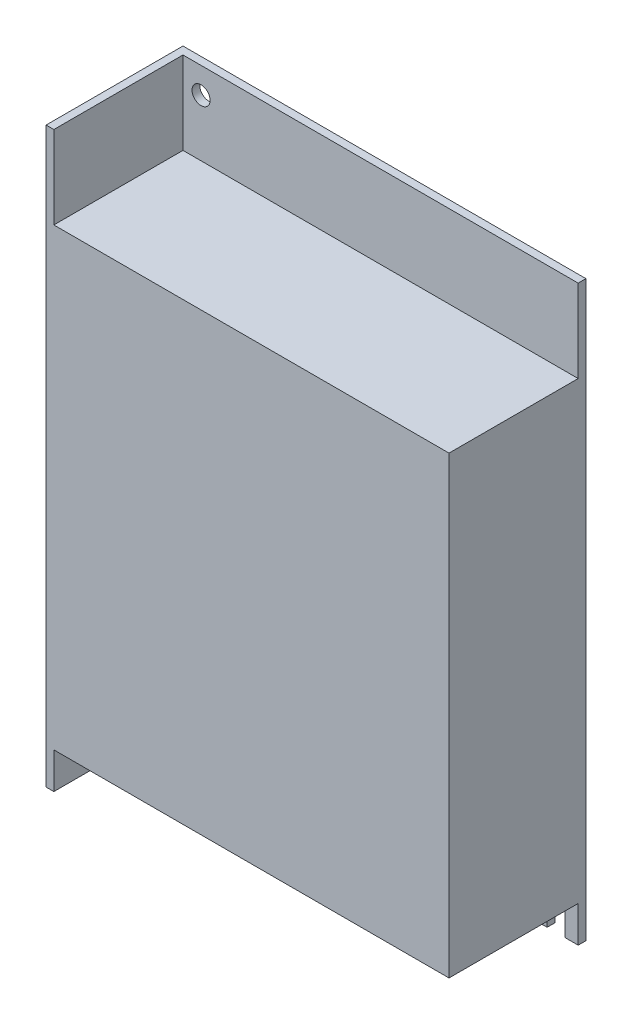
SolidWorks part; units mm, degrees
ref_plane "Plan de face" through (0, 0, 0) normal (0, 0, 1) x (1, 0, 0)
ref_plane "Plan de dessus" through (0, 0, 0) normal (0, 1, 0) x (1, 0, 0)
ref_plane "Plan de droite" through (0, 0, 0) normal (1, 0, 0) x (0, 0, -1)
sketch "Esquisse1" plane through (0, 0, 0) normal (0, 0, 1) x (1, 0, 0)
  line L0 (72, 4.25) -> (72, 0)
  line L1 (0, 0) -> (78, 0)
  line L2 (0, 0) -> (0, 111)
  line L3 (0, 111) -> (78, 111)
  line L4 (78, 0) -> (78, 111)
  line L5 (75.5, 4.25) -> (75.5, 0)
  circle A0 centre (73.75, 4.25) radius 1.75
  circle A1 centre (5, 106) radius 1.75
  dimension "D3" = 3.5
  dimension "D4" = 3.5
  dimension "D1" = 78
  dimension "D2" = 111
  dimension "D5" = 4.25
  dimension "D6" = 72
  dimension "D7" = 73
  dimension "D8" = 5
extrude "Boss.-Extru.1" add sketch "Esquisse1" along normal blind 1.5 contours A0 L5 L1 L4 L3 L2 L0 A1
sketch "Esquisse2" plane through (0, 0, 1.5) normal (0, 0, 1) x (1, 0, 0)
  line L0 (0, 0) -> (72, 0) construction
  line L1 (0, 111) -> (1.5, 111)
  line L2 (0, 111) -> (0, 0)
  line L3 (0, 0) -> (1.5, 0)
  line L4 (1.5, 111) -> (1.5, 0)
  line L5 (78, 0) -> (78, 111) construction
  line L6 (1.5, 7) -> (78, 7)
  line L7 (1.5, 7) -> (1.5, 95)
  line L8 (1.5, 95) -> (78, 95)
  line L9 (78, 7) -> (78, 95)
  line M10 (78, 0) -> (78, 111)
  line M11 (78, 111) -> (0, 111)
  line M12 (0, 111) -> (0, 0)
  line M13 (0, 0) -> (72, 0)
  dimension "D1" = 0
  dimension "D2" = 1.5
  dimension "D3" = 88
  dimension "D4" = 7
extrude "Boss.-Extru.2" add sketch "Esquisse2" along normal blind 25 contours L8 L4 L6 M10 | L4 M11 M12 M13
